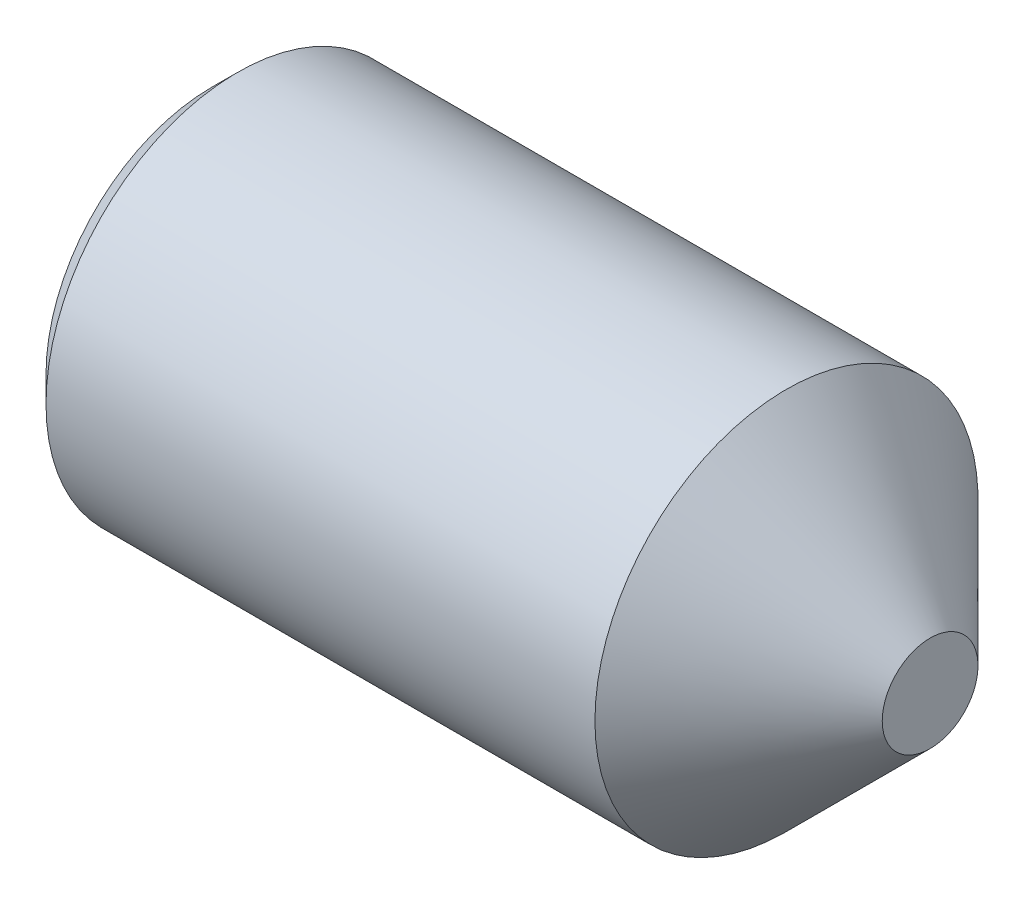
SolidWorks part; units mm, degrees
ref_plane "前视" through (0, 0, 0) normal (0, 0, 1) x (1, 0, 0)
ref_plane "上视" through (0, 0, 0) normal (0, 1, 0) x (1, 0, 0)
ref_plane "右视" through (0, 0, 0) normal (1, 0, 0) x (0, 0, -1)
sketch "尺寸草图" plane through (0, 0, 0) normal (0, 0, 1) x (1, 0, 0)
  line L0 (0, 0) -> (25, 0) construction
  point P3 (21, 0)
  point P4 (15.851, 0)
  point P5 (13.856, 0)
  point P6 (16, 0)
  point P7 (10, 0)
  point P8 (23, 0)
  point P9 (8, 0)
  dimension "l" = 25
  dimension "d" = 16
  dimension "df" = 13.856
  dimension "dt" = 4
  dimension "e" = 9.149
  dimension "t" = 10
  dimension "P" = 2
  dimension "s" = 8
sketch "草图1" plane through (0, 0, 0) normal (0, 0, 1) x (1, 0, 0)
  line L0 (-1.4105, 0) -> (5.3344, 0) construction
  line L1 (0, 0) -> (30, 0)
  line L2 (30, 0) -> (30, 2)
  line L3 (30, 2) -> (24, 8)
  line L4 (24, 8) -> (1.072, 8)
  line L5 (1.072, 8) -> (0, 6.928)
  line L6 (0, 6.928) -> (0, 0)
  dimension "D1" = 45
  dimension "l" = 30
  dimension "df" = 13.856
  dimension "d" = 16
  dimension "dt" = 4
  dimension "D2" = 45
revolve "基体-旋转" add sketch "草图1" angle 360 about L0
cosmetic thread "装饰螺纹线1" parameters "D1"=19, "df"=13.856
sketch "草图2" plane through (0, 0, 0) normal (-1, 0, 0) x (0, 0, 1)
  line L1 (4.5745, 0) -> (2.2872, 3.9616)
  line L2 (2.2872, 3.9616) -> (-2.2872, 3.9616)
  line L3 (-2.2872, 3.9616) -> (-4.5745, 0)
  line L4 (-4.5745, 0) -> (-2.2872, -3.9616)
  line L5 (-2.2872, -3.9616) -> (2.2872, -3.9616)
  line L6 (2.2872, -3.9616) -> (4.5745, 0)
  circle A0 centre (0, 0) radius 3.9616 construction
  dimension "e" = 9.149
extrude "切除-拉伸1" cut sketch "草图2" against normal blind 10
sketch "草图3" plane through (0, 0, 0) normal (0, 0, 1) x (1, 0, 0)
  line L0 (10, 3.9616) -> (12.2873, 0)
  line L1 (-1.4105, 0) -> (5.3344, 0) construction
  line L2 (12.2873, 0) -> (10, 0)
  line L3 (10, 0) -> (10, 3.9616)
  line L4 (-0.1213, 0) -> (1.4124, 0) construction
  dimension "D1" = 60
revolve "切除-旋转1" cut sketch "草图3" angle 360 about L4
sketch "草图4" plane through (0, 0, 0) normal (0, 0, 1) x (1, 0, 0)
  line L0 (1.072, 8) -> (3.072, 8)
  line L1 (3.072, 8) -> (2.0612, 6.268)
  line L2 (2.0612, 6.268) -> (1.072, 8)
  line L3 (24, 8) -> (1.072, 8) construction
  line L5 (1.072, 8) -> (1.072, -8) construction
  line L6 (-0.1526, 0) -> (1.162, 0) construction
  line L7 (-1.4105, 0) -> (5.3344, 0) construction
  dimension "D1" = 1.732
  dimension "P" = 2
  dimension "D2" = 60
revolve "切除-旋转2" [suppressed] cut sketch "草图4" angle 360 about L6
pattern_linear "阵列(线性)1" [suppressed] count 10
